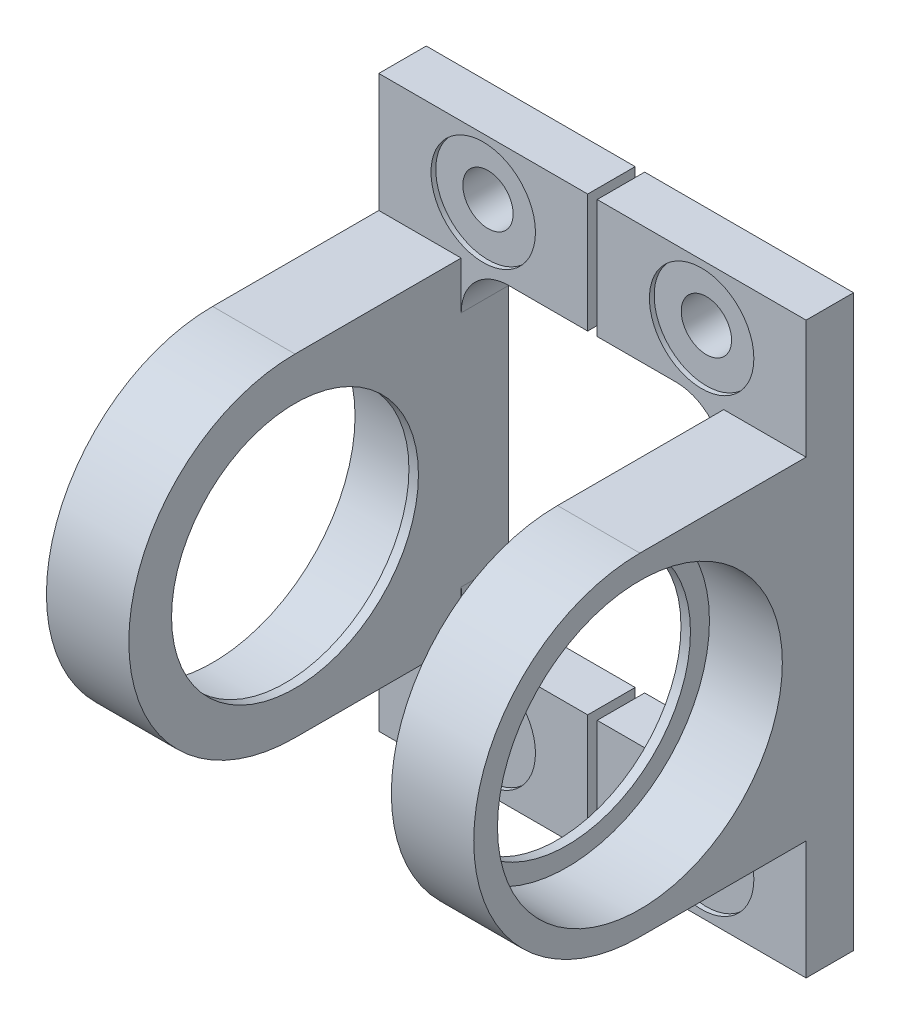
SolidWorks part; units mm, degrees
ref_plane "前视基准面" through (0, 0, 0) normal (0, 0, 1) x (1, 0, 0)
ref_plane "上视基准面" through (0, 0, 0) normal (0, 1, 0) x (1, 0, 0)
ref_plane "右视基准面" through (0, 0, 0) normal (1, 0, 0) x (0, 0, -1)
sketch "草图2" plane through (0, 0, 0) normal (0, 0, 1) x (1, 0, 0)
  line L0 (-14.7736, 24.3382) -> (-14.7736, -35.6618)
  line L1 (-14.7736, -35.6618) -> (30.2264, -35.6618)
  line L2 (7.7264, -35.6618) -> (7.7264, -23.1618)
  line L3 (21.55, -23.1618) -> (-6.0971, -23.1618)
  line L4 (-6.0971, -23.1618) -> (-6.0971, 11.8382)
  line L5 (-6.0971, 11.8382) -> (21.55, 11.8382)
  line L6 (7.7264, 11.8382) -> (7.7264, 24.3382)
  line L7 (30.2264, 24.3382) -> (-14.7736, 24.3382)
  line L8 (7.7264, 28.8603) -> (7.7264, -39.8897) construction
  line L9 (21.55, -23.1618) -> (21.55, 11.8382)
  line L10 (30.2264, 24.3382) -> (30.2264, -35.6618)
  line L11 (-18.1559, -5.6618) -> (33.2411, -5.6618) construction
  point P16 (-6.0971, -5.6618)
  point P17 (-14.7736, -5.6618)
  dimension "D1" = 45
  dimension "D2" = 35
  dimension "D3" = 60
extrude "凸台-拉伸2" add sketch "草图2" along normal blind 5 contours L6 L7 L0 L1 L2 L3 L4 L5 | L10 L7 L6 L5 L9 L3 L2 L1
sketch "草图4" plane through (0, 0, 5) normal (0, 0, 1) x (1, 0, 0)
  line L0 (-18.165, -5.6618) -> (33.9165, -5.6618) construction
  line L1 (-14.7736, 24.3382) -> (-14.7736, -35.6618) construction
  line L2 (-14.7736, -23.1618) -> (-6.0971, -23.1618)
  line L3 (-14.7736, -23.1618) -> (-14.7736, 11.8382)
  line L4 (-14.7736, 11.8382) -> (-6.0971, 11.8382)
  line L5 (-6.0971, -23.1618) -> (-6.0971, 11.8382)
  line L6 (-6.0971, -23.1618) -> (-6.0971, 11.8382) construction
  line L7 (7.7264, -39.813) -> (7.7264, 28.1228) construction
  line L8 (30.2264, 11.8382) -> (21.55, 11.8382)
  line L9 (21.55, -23.1618) -> (21.55, 11.8382)
  line L10 (30.2264, -23.1618) -> (21.55, -23.1618)
  line L11 (30.2264, -23.1618) -> (30.2264, 11.8382)
  point P17 (-14.7736, -5.6618)
  dimension "D1" = 35
extrude "凸台-拉伸15" add sketch "草图4" along normal blind 35
sketch "草图5" plane through (-14.7736, 0, 0) normal (-1, 0, 0) x (0, 0, 1)
  line L0 (0, -5.6618) -> (40, -5.6618)
  line L1 (0, 24.3382) -> (0, -35.6618) construction
  line L2 (40, 11.8382) -> (40, -23.1618) construction
  line L3 (22.5, 11.8382) -> (40, 11.8382)
  line L4 (40, 11.8382) -> (40, -23.1618)
  line L5 (40, -23.1618) -> (22.5, -23.1618)
  circle A0 centre (22.5, -5.6618) radius 17.5
  line M5 (5, -23.1618) -> (40, -23.1618)
  line M6 (40, -23.1618) -> (40, 11.8382)
  line M7 (40, 11.8382) -> (5, 11.8382)
  dimension "D1" = 35
extrude "切除-拉伸1" cut sketch "草图5" against normal blind 45 contours A0 M5 M6 | A0 M6 M7
sketch "草图6" plane through (-14.7736, 0, 0) normal (-1, 0, 0) x (0, 0, 1)
  circle A0 centre (22.5, -5.6618) radius 15
extrude "切除-拉伸2" cut sketch "草图6" against normal blind 45
fillet "圆角1" radius 5 4 edges at (-6.0971, 11.8382, 2.5) (21.55, 11.8382, 2.5) (-6.0971, -23.1618, 2.5) (21.55, -23.1618, 2.5)
sketch "草图7" plane through (-6.0971, 0, 0) normal (1, 0, 0) x (0, 0, -1)
  circle A0 centre (-22.5, -5.6618) radius 15
  circle A1 centre (-22.5, -5.6618) radius 13
extrude "凸台-拉伸16" add sketch "草图7" against normal blind 1
sketch "草图8" plane through (21.55, 0, 0) normal (-1, 0, 0) x (0, 0, 1)
  circle A0 centre (22.5, -5.6618) radius 15
  circle A1 centre (22.5, -5.6618) radius 13
extrude "凸台-拉伸17" add sketch "草图8" against normal blind 1
sketch "草图9" plane through (0, 0, 5) normal (0, 0, 1) x (1, 0, 0)
  line L0 (7.7264, -35.6618) -> (7.7264, 24.3382) construction
  line L1 (-14.7736, -35.6618) -> (30.2264, -35.6618) construction
  line L2 (30.2264, 24.3382) -> (-14.7736, 24.3382) construction
  line L3 (8.2264, 24.3382) -> (7.2264, 24.3382)
  line L4 (7.2264, 24.3382) -> (7.2264, 11.8382)
  line L5 (-1.0971, 11.8382) -> (16.55, 11.8382) construction
  line L6 (7.2264, 11.8382) -> (8.2264, 11.8382)
  line L7 (8.2264, -35.6618) -> (7.2264, -35.6618)
  line L8 (7.2264, -35.6618) -> (7.2264, -23.1618)
  line L9 (16.55, -23.1618) -> (-1.0971, -23.1618) construction
  line L10 (7.2264, -23.1618) -> (8.2264, -23.1618)
  line L11 (8.2264, -35.6618) -> (8.2264, -23.1618)
  line L12 (8.2264, 24.3382) -> (8.2264, 11.8382)
  point P17 (7.7264, -23.1618)
  point P19 (7.7264, 11.8382)
  dimension "D1" = 1
  dimension "D2" = 1
extrude "切除-拉伸3" cut sketch "草图9" against normal blind 5
sketch "草图11" plane through (0, 0, 5) normal (0, 0, 1) x (1, 0, 0)
  line L0 (-14.7736, 18.0882) -> (7.2264, 18.0882)
  line L1 (-14.7736, 24.3382) -> (-14.7736, 11.8382) construction
  line L2 (7.2264, 24.3382) -> (7.2264, 11.8382) construction
  line L4 (8.2264, 18.0882) -> (30.2264, 18.0882)
  line L5 (8.2264, 11.8382) -> (8.2264, 24.3382) construction
  line L7 (30.2264, 24.3382) -> (30.2264, 11.8382) construction
  line L10 (-14.7736, -29.4118) -> (7.2264, -29.4118)
  line L11 (-14.7736, -23.1618) -> (-14.7736, -35.6618) construction
  line L12 (7.2264, -23.1618) -> (7.2264, -35.6618) construction
  line L13 (8.2264, -29.4118) -> (30.2264, -29.4118)
  line L14 (8.2264, -35.6618) -> (8.2264, -23.1618) construction
  line L15 (30.2264, -23.1618) -> (30.2264, -35.6618) construction
  point P24 (-3.7736, 18.0882)
  point P25 (19.2264, 18.0882)
  point P26 (-3.7736, -29.4118)
  point P27 (19.2264, -29.4118)
hole_wizard "打孔尺寸(%根据六角头螺)栓 全螺纹的类型1" positions "3D草图3" profile "草图13" counterbore size "M5" standard "GB"
sketch3d "3D草图3"
  point P0 (-3.7736, 18.0882, 5)
  point P3 (19.2264, 18.0882, 5)
  point P6 (-3.7736, -29.4118, 5)
  point P9 (19.2264, -29.4118, 5)
sketch "草图13" plane through (-3.7736, 18.0882, 5) normal (1, 0, 0) x (0, -1, 0)
  line L0 (0, 0) -> (0, 6.5923)
  line L1 (0, 6.5923) -> (2.65, 5)
  line L2 (2.65, 5) -> (2.65, 0.5)
  line L3 (2.65, 0.5) -> (5.5, 0.5)
  line L4 (5.5, 0.5) -> (5.5, 0)
  line L5 (5.5, 0) -> (0, 0)
  line L10 (0, 6.5923) -> (-2.65, 5) construction
  line L11 (0, -6.35) -> (0, 107.95) construction
  dimension "孔直径" = 5.3
  dimension "孔深度" = 5
  dimension "柱形沉头孔直径" = 11
  dimension "柱形沉头孔深度" = 0.5
  dimension "导头角度" = 118
